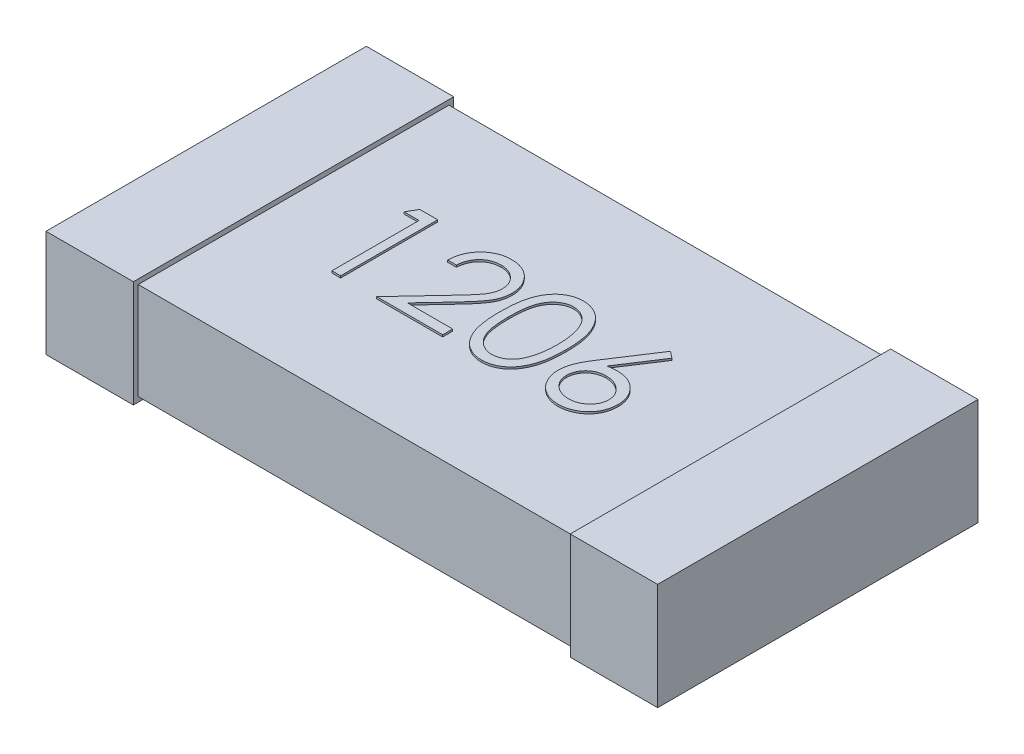
SolidWorks part; units mm, degrees
ref_plane "Front Plane" through (0, 0, 0) normal (0, 0, 1) x (1, 0, 0)
ref_plane "Top Plane" through (0, 0, 0) normal (0, 1, 0) x (1, 0, 0)
ref_plane "Right Plane" through (0, 0, 0) normal (1, 0, 0) x (0, 0, -1)
sketch "Sketch1" plane through (0, 0, 0) normal (0, 1, 0) x (1, 0, 0)
  line L1 (-1.55, -0.8) -> (1.55, -0.8)
  line L2 (-1.55, -0.8) -> (-1.55, 0.8)
  line L3 (-1.55, 0.8) -> (1.55, 0.8)
  line L4 (1.55, -0.8) -> (1.55, 0.8)
  line L5 (-1.55, -0.8) -> (1.55, 0.8) construction
  line L6 (-1.55, 0.8) -> (1.55, -0.8) construction
  point P0 (0, 0)
  dimension "D1" = 1.6
  dimension "D2" = 3.1
extrude "Boss-Extrude1" add sketch "Sketch1" along normal blind 0.5
sketch "Sketch4" plane through (0, 0, 0.8) normal (0, 0, 1) x (1, 0, 0)
  line L0 (-1.125, 0.5) -> (-1.55, 0.5)
  line L1 (-1.55, 0.5) -> (1.55, 0.5) construction
  line L2 (-1.55, 0.5) -> (-1.55, 0)
  line L3 (-1.55, 0) -> (-1.125, 0)
  line L4 (-1.55, 0) -> (1.55, 0) construction
  line L5 (-1.125, 0) -> (-1.125, -0.025)
  line L6 (-1.125, -0.025) -> (-1.575, -0.025)
  line L7 (-1.575, -0.025) -> (-1.575, 0.525)
  line L8 (-1.575, 0.525) -> (-1.125, 0.525)
  line L9 (-1.125, 0.525) -> (-1.125, 0.5)
  dimension "D1" = 0.45
  dimension "D2" = 0.025
  dimension "D3" = 0.025
  dimension "D4" = 0.025
  dimension "D5" = 0.45
extrude "Boss-Extrude5" add sketch "Sketch4" against normal blind 1.6
sketch "Sketch5" plane through (0, 0, 0.8) normal (0, 0, 1) x (1, 0, 0)
  line L1 (-1.575, 0.525) -> (-1.125, 0.525)
  line L2 (-1.575, 0.525) -> (-1.575, -0.025)
  line L3 (-1.575, -0.025) -> (-1.125, -0.025)
  line L4 (-1.125, 0.525) -> (-1.125, -0.025)
extrude "Boss-Extrude6" add sketch "Sketch5" along normal blind 0.025
sketch "Sketch6" plane through (0, 0, -0.8) normal (0, 0, -1) x (-1, 0, 0)
  line L1 (1.575, 0.525) -> (1.125, 0.525)
  line L2 (1.575, 0.525) -> (1.575, -0.025)
  line L3 (1.575, -0.025) -> (1.125, -0.025)
  line L4 (1.125, 0.525) -> (1.125, -0.025)
extrude "Boss-Extrude7" add sketch "Sketch6" along normal blind 0.025
sketch "Sketch7" plane through (0, 0, 0.8) normal (0, 0, 1) x (1, 0, 0)
  line L0 (1.125, 0.5) -> (1.55, 0.5)
  line L1 (-1.125, 0.5) -> (1.55, 0.5) construction
  line L2 (1.55, 0.5) -> (1.55, 0)
  line L3 (1.55, 0) -> (1.125, 0)
  line L4 (-1.125, 0) -> (1.55, 0) construction
  line L5 (1.125, 0) -> (1.125, -0.025)
  line L6 (1.125, -0.025) -> (1.575, -0.025)
  line L7 (1.575, -0.025) -> (1.575, 0.525)
  line L8 (1.575, 0.525) -> (1.125, 0.525)
  line L9 (1.125, 0.525) -> (1.125, 0.5)
  dimension "D1" = 0.45
  dimension "D2" = 0.45
  dimension "D3" = 0.025
  dimension "D4" = 0.025
  dimension "D5" = 0.025
extrude "Boss-Extrude8" add sketch "Sketch7" against normal blind 1.6
sketch "Sketch8" plane through (0, 0, 0.8) normal (0, 0, 1) x (1, 0, 0)
  line L1 (1.575, 0.525) -> (1.125, 0.525)
  line L2 (1.575, 0.525) -> (1.575, -0.025)
  line L3 (1.575, -0.025) -> (1.125, -0.025)
  line L4 (1.125, 0.525) -> (1.125, -0.025)
extrude "Boss-Extrude9" add sketch "Sketch8" along normal blind 0.025
sketch "Sketch9" plane through (0, 0, -0.8) normal (0, 0, -1) x (-1, 0, 0)
  line L1 (-1.575, 0.525) -> (-1.125, 0.525)
  line L2 (-1.575, 0.525) -> (-1.575, -0.025)
  line L3 (-1.575, -0.025) -> (-1.125, -0.025)
  line L4 (-1.125, 0.525) -> (-1.125, -0.025)
extrude "Boss-Extrude10" add sketch "Sketch9" along normal blind 0.025
sketch "Sketch10" plane through (0, 0.5, 0) normal (0, 1, 0) x (1, 0, 0)
  line L0 (-0.8506, -0.25) -> (0.8506, -0.25) construction
  text T0 "1206" font "Century Gothic" height 0.5
  point P2 (0, -0.25)
  dimension "D1" = 0.25
extrude "Boss-Extrude11" add sketch "Sketch10" along normal blind 0.01
